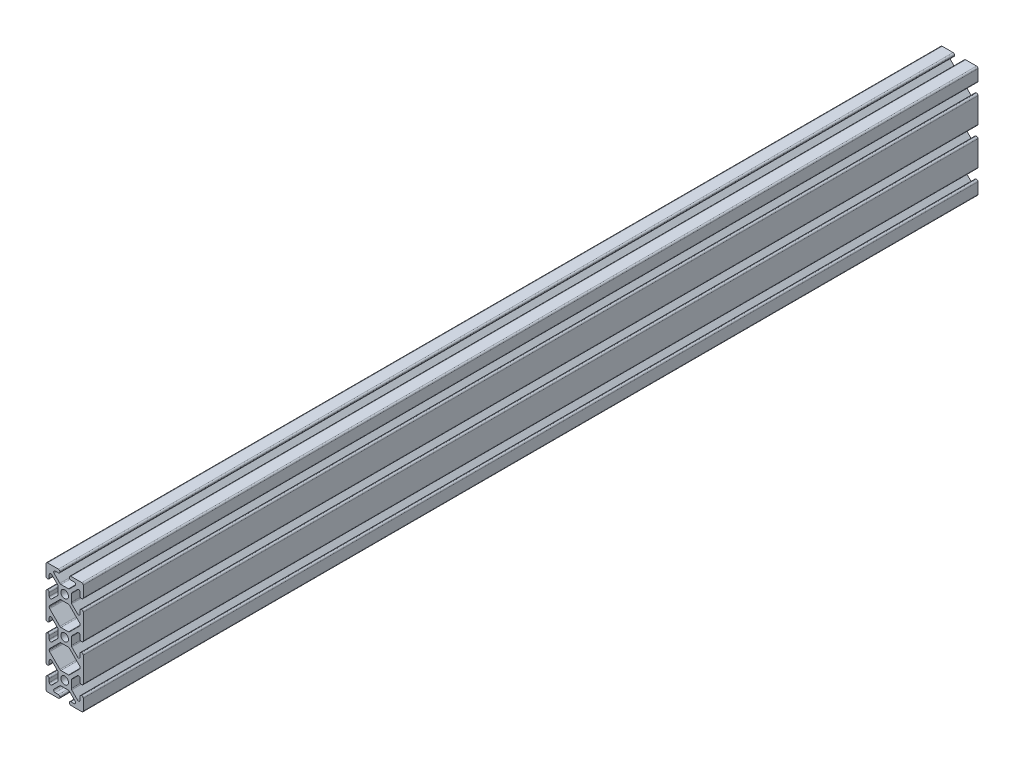
SolidWorks part; units mm, degrees
ref_plane "Front Plane" through (0, 0, 0) normal (0, 0, 1) x (1, 0, 0)
ref_plane "Top Plane" through (0, 0, 0) normal (0, 1, 0) x (1, 0, 0)
ref_plane "Right Plane" through (0, 0, 0) normal (1, 0, 0) x (0, 0, -1)
sketch "Sketch1" plane through (0, 0, 0) normal (0, 0, 1) x (1, 0, 0)
  line L0 (-12.7, 38.1) -> (-12.7, 12.7) construction
  line L1 (-12.7, -38.1) -> (12.7, -38.1) construction
  line L2 (-12.7, 12.7) -> (-12.7, -12.7) construction
  line L3 (-12.7, 38.1) -> (12.7, 38.1) construction
  line L4 (-12.7, -12.7) -> (-12.7, -38.1) construction
  line L5 (-12.7, -38.1) -> (12.7, 38.1) construction
  line L6 (-12.7, 38.1) -> (12.7, -38.1) construction
  line L7 (12.7, 38.1) -> (12.7, 12.7) construction
  line L8 (12.7, 12.7) -> (12.7, -12.7) construction
  line L9 (12.7, -12.7) -> (12.7, -38.1) construction
  line L10 (-12.7, 12.7) -> (12.7, 12.7) construction
  line L11 (-12.7, -12.7) -> (12.7, -12.7) construction
  line L12 (12.7, -12.7) -> (-12.7, -38.1) construction
  line L13 (12.7, -38.1) -> (-12.7, -12.7) construction
  line L14 (0, 38.1) -> (0, -38.1) construction
  line L15 (12.7, 12.7) -> (-12.7, 38.1) construction
  line L16 (12.7, 38.1) -> (-12.7, 12.7) construction
  line L17 (-12.7, 37.084) -> (-12.7, 29.6672)
  line L18 (-11.684, 28.6512) -> (-11.5062, 28.6512)
  line L19 (-10.4902, 29.6672) -> (-10.4902, 31.8748)
  line L20 (-8.7558, 32.5932) -> (-4.8188, 28.6562)
  line L21 (-4.5212, 27.9378) -> (-4.5212, 22.8622)
  line L22 (-4.8188, 22.1438) -> (-8.7558, 18.2068)
  line L23 (-10.4902, 18.9252) -> (-10.4902, 21.1328)
  line L24 (-11.5062, 22.1488) -> (-11.684, 22.1488)
  line L25 (-12.7, 21.1328) -> (-12.7, 4.2672)
  line L26 (-12.7, 0) -> (12.7, 0) construction
  line L27 (-12.7, -25.4) -> (12.7, -25.4) construction
  line L28 (-12.7, 25.4) -> (12.7, 25.4) construction
  line L29 (4.2672, 38.1) -> (11.684, 38.1)
  line L30 (3.2512, 36.9062) -> (3.2512, 37.084)
  line L31 (6.4748, 35.8902) -> (4.2672, 35.8902)
  line L32 (3.2562, 30.2188) -> (7.1932, 34.1558)
  line L33 (-2.5378, 29.9212) -> (2.5378, 29.9212)
  line L34 (-7.1932, 34.1558) -> (-3.2562, 30.2188)
  line L35 (-4.2672, 35.8902) -> (-6.4748, 35.8902)
  line L36 (-3.2512, 37.084) -> (-3.2512, 36.9062)
  line L37 (-11.684, 38.1) -> (-4.2672, 38.1)
  line L38 (4.5212, 2.5378) -> (4.5212, -2.5378)
  line L39 (11.5062, 22.1488) -> (11.684, 22.1488)
  line L40 (10.4902, 18.9252) -> (10.4902, 21.1328)
  line L41 (4.8188, 22.1438) -> (8.7558, 18.2068)
  line L42 (4.5212, 27.9378) -> (4.5212, 22.8622)
  line L43 (8.7558, 32.5932) -> (4.8188, 28.6562)
  line L44 (10.4902, 29.6672) -> (10.4902, 31.8748)
  line L45 (11.684, 28.6512) -> (11.5062, 28.6512)
  line L46 (12.7, 37.084) -> (12.7, 29.6672)
  line L47 (-10.4902, 12.4736) -> (-10.4902, 12.9264)
  line L48 (-10.1926, 13.6448) -> (-3.2562, 20.5812)
  line L49 (-2.5378, 20.8788) -> (2.5378, 20.8788)
  line L50 (10.4902, 12.4736) -> (10.4902, 12.9264)
  line L51 (10.1926, 13.6448) -> (3.2562, 20.5812)
  line L52 (10.1926, 11.7552) -> (3.2562, 4.8188)
  line L53 (-2.5378, 4.5212) -> (2.5378, 4.5212)
  line L54 (-10.1926, 11.7552) -> (-3.2562, 4.8188)
  line L55 (-2.5378, -4.5212) -> (2.5378, -4.5212)
  line L56 (-10.1926, -11.7552) -> (-3.2562, -4.8188)
  line L57 (10.1926, -11.7552) -> (3.2562, -4.8188)
  line L58 (10.4902, -12.4736) -> (10.4902, -12.9264)
  line L59 (10.1926, -13.6448) -> (3.2562, -20.5812)
  line L60 (-2.5378, -20.8788) -> (2.5378, -20.8788)
  line L61 (-10.1926, -13.6448) -> (-3.2562, -20.5812)
  line L62 (-10.4902, -12.4736) -> (-10.4902, -12.9264)
  line L63 (4.8188, -3.2562) -> (8.7558, -7.1932)
  line L64 (11.5062, -22.1488) -> (11.684, -22.1488)
  line L65 (10.4902, -18.9252) -> (10.4902, -21.1328)
  line L66 (4.8188, -22.1438) -> (8.7558, -18.2068)
  line L67 (4.5212, -27.9378) -> (4.5212, -22.8622)
  line L68 (8.7558, -32.5932) -> (4.8188, -28.6562)
  line L69 (10.4902, -29.6672) -> (10.4902, -31.8748)
  line L70 (11.684, -28.6512) -> (11.5062, -28.6512)
  line L71 (12.7, -37.084) -> (12.7, -29.6672)
  line L72 (3.2512, -36.9062) -> (3.2512, -37.084)
  line L73 (6.4748, -35.8902) -> (4.2672, -35.8902)
  line L74 (3.2562, -30.2188) -> (7.1932, -34.1558)
  line L75 (-2.5378, -29.9212) -> (2.5378, -29.9212)
  line L76 (-7.1932, -34.1558) -> (-3.2562, -30.2188)
  line L77 (-4.2672, -35.8902) -> (-6.4748, -35.8902)
  line L78 (-3.2512, -37.084) -> (-3.2512, -36.9062)
  line L79 (-11.684, -38.1) -> (-4.2672, -38.1)
  line L80 (4.2672, -38.1) -> (11.684, -38.1)
  line L81 (4.8188, 3.2562) -> (8.7558, 7.1932)
  line L82 (-11.5062, -22.1488) -> (-11.684, -22.1488)
  line L83 (-10.4902, -18.9252) -> (-10.4902, -21.1328)
  line L84 (-4.8188, -22.1438) -> (-8.7558, -18.2068)
  line L85 (-4.5212, -27.9378) -> (-4.5212, -22.8622)
  line L86 (-8.7558, -32.5932) -> (-4.8188, -28.6562)
  line L87 (-10.4902, -29.6672) -> (-10.4902, -31.8748)
  line L88 (-11.684, -28.6512) -> (-11.5062, -28.6512)
  line L89 (-12.7, -37.084) -> (-12.7, -29.6672)
  line L90 (-4.8188, 3.2562) -> (-8.7558, 7.1932)
  line L91 (-10.4902, 6.4748) -> (-10.4902, 4.2672)
  line L92 (-11.5062, 3.2512) -> (-11.684, 3.2512)
  line L93 (-4.5212, 2.5378) -> (-4.5212, -2.5378)
  line L94 (-12.7, -21.1328) -> (-12.7, -4.2672)
  line L95 (-4.8188, -3.2562) -> (-8.7558, -7.1932)
  line L96 (-10.4902, -6.4748) -> (-10.4902, -4.2672)
  line L97 (-11.5062, -3.2512) -> (-11.684, -3.2512)
  line L98 (10.4902, -6.4748) -> (10.4902, -4.2672)
  line L99 (10.4902, 6.4748) -> (10.4902, 4.2672)
  line L100 (11.5062, 3.2512) -> (11.684, 3.2512)
  line L101 (11.5062, -3.2512) -> (11.684, -3.2512)
  line L102 (12.7, -21.1328) -> (12.7, -4.2672)
  line L103 (12.7, 21.1328) -> (12.7, 4.2672)
  circle A0 centre (0, 25.4) radius 2.6035
  circle A1 centre (0, 0) radius 2.6035
  circle A2 centre (0, -25.4) radius 2.6035
  arc A3 (-12.7, 21.1328) -> (-11.684, 22.1488) centre (-11.684, 21.1328) cw
  arc A4 (-11.5062, 22.1488) -> (-10.4902, 21.1328) centre (-11.5062, 21.1328) cw
  arc A5 (-10.4902, 18.9252) -> (-8.7558, 18.2068) centre (-9.4742, 18.9252) ccw
  arc A6 (-4.8188, 22.1438) -> (-4.5212, 22.8622) centre (-5.5372, 22.8622) ccw
  arc A7 (-4.5212, 27.9378) -> (-4.8188, 28.6562) centre (-5.5372, 27.9378) ccw
  arc A8 (-8.7558, 32.5932) -> (-10.4902, 31.8748) centre (-9.4742, 31.8748) ccw
  arc A9 (-10.4902, 29.6672) -> (-11.5062, 28.6512) centre (-11.5062, 29.6672) cw
  arc A10 (-11.684, 28.6512) -> (-12.7, 29.6672) centre (-11.684, 29.6672) cw
  arc A11 (4.2672, 38.1) -> (3.2512, 37.084) centre (4.2672, 37.084) ccw
  arc A12 (3.2512, 36.9062) -> (4.2672, 35.8902) centre (4.2672, 36.9062) ccw
  arc A13 (6.4748, 35.8902) -> (7.1932, 34.1558) centre (6.4748, 34.8742) cw
  arc A14 (3.2562, 30.2188) -> (2.5378, 29.9212) centre (2.5378, 30.9372) cw
  arc A15 (-2.5378, 29.9212) -> (-3.2562, 30.2188) centre (-2.5378, 30.9372) cw
  arc A16 (-7.1932, 34.1558) -> (-6.4748, 35.8902) centre (-6.4748, 34.8742) cw
  arc A17 (-4.2672, 35.8902) -> (-3.2512, 36.9062) centre (-4.2672, 36.9062) ccw
  arc A18 (-3.2512, 37.084) -> (-4.2672, 38.1) centre (-4.2672, 37.084) ccw
  arc A19 (12.7, 21.1328) -> (11.684, 22.1488) centre (11.684, 21.1328) ccw
  arc A20 (11.5062, 22.1488) -> (10.4902, 21.1328) centre (11.5062, 21.1328) ccw
  arc A21 (10.4902, 18.9252) -> (8.7558, 18.2068) centre (9.4742, 18.9252) cw
  arc A22 (4.8188, 22.1438) -> (4.5212, 22.8622) centre (5.5372, 22.8622) cw
  arc A23 (4.5212, 27.9378) -> (4.8188, 28.6562) centre (5.5372, 27.9378) cw
  arc A24 (8.7558, 32.5932) -> (10.4902, 31.8748) centre (9.4742, 31.8748) cw
  arc A25 (10.4902, 29.6672) -> (11.5062, 28.6512) centre (11.5062, 29.6672) ccw
  arc A26 (11.684, 28.6512) -> (12.7, 29.6672) centre (11.684, 29.6672) ccw
  arc A27 (12.7, 37.084) -> (11.684, 38.1) centre (11.684, 37.084) ccw
  arc A28 (-11.684, 38.1) -> (-12.7, 37.084) centre (-11.684, 37.084) ccw
  arc A29 (-10.1926, 13.6448) -> (-10.4902, 12.9264) centre (-9.4742, 12.9264) ccw
  arc A30 (-2.5378, 20.8788) -> (-3.2562, 20.5812) centre (-2.5378, 19.8628) ccw
  arc A31 (10.1926, 13.6448) -> (10.4902, 12.9264) centre (9.4742, 12.9264) cw
  arc A32 (2.5378, 20.8788) -> (3.2562, 20.5812) centre (2.5378, 19.8628) cw
  arc A33 (10.1926, 11.7552) -> (10.4902, 12.4736) centre (9.4742, 12.4736) ccw
  arc A34 (2.5378, 4.5212) -> (3.2562, 4.8188) centre (2.5378, 5.5372) ccw
  arc A35 (-2.5378, 4.5212) -> (-3.2562, 4.8188) centre (-2.5378, 5.5372) cw
  arc A36 (-10.1926, 11.7552) -> (-10.4902, 12.4736) centre (-9.4742, 12.4736) cw
  arc A37 (2.5378, -4.5212) -> (3.2562, -4.8188) centre (2.5378, -5.5372) cw
  arc A38 (-2.5378, -4.5212) -> (-3.2562, -4.8188) centre (-2.5378, -5.5372) ccw
  arc A39 (10.1926, -11.7552) -> (10.4902, -12.4736) centre (9.4742, -12.4736) cw
  arc A40 (10.1926, -13.6448) -> (10.4902, -12.9264) centre (9.4742, -12.9264) ccw
  arc A41 (2.5378, -20.8788) -> (3.2562, -20.5812) centre (2.5378, -19.8628) ccw
  arc A42 (-2.5378, -20.8788) -> (-3.2562, -20.5812) centre (-2.5378, -19.8628) cw
  arc A43 (-10.1926, -13.6448) -> (-10.4902, -12.9264) centre (-9.4742, -12.9264) cw
  arc A44 (-10.1926, -11.7552) -> (-10.4902, -12.4736) centre (-9.4742, -12.4736) ccw
  arc A45 (12.7, -21.1328) -> (11.684, -22.1488) centre (11.684, -21.1328) cw
  arc A46 (11.5062, -22.1488) -> (10.4902, -21.1328) centre (11.5062, -21.1328) cw
  arc A47 (10.4902, -18.9252) -> (8.7558, -18.2068) centre (9.4742, -18.9252) ccw
  arc A48 (4.8188, -22.1438) -> (4.5212, -22.8622) centre (5.5372, -22.8622) ccw
  arc A49 (4.5212, -27.9378) -> (4.8188, -28.6562) centre (5.5372, -27.9378) ccw
  arc A50 (8.7558, -32.5932) -> (10.4902, -31.8748) centre (9.4742, -31.8748) ccw
  arc A51 (10.4902, -29.6672) -> (11.5062, -28.6512) centre (11.5062, -29.6672) cw
  arc A52 (11.684, -28.6512) -> (12.7, -29.6672) centre (11.684, -29.6672) cw
  arc A53 (4.2672, -38.1) -> (3.2512, -37.084) centre (4.2672, -37.084) cw
  arc A54 (3.2512, -36.9062) -> (4.2672, -35.8902) centre (4.2672, -36.9062) cw
  arc A55 (6.4748, -35.8902) -> (7.1932, -34.1558) centre (6.4748, -34.8742) ccw
  arc A56 (3.2562, -30.2188) -> (2.5378, -29.9212) centre (2.5378, -30.9372) ccw
  arc A57 (-2.5378, -29.9212) -> (-3.2562, -30.2188) centre (-2.5378, -30.9372) ccw
  arc A58 (-7.1932, -34.1558) -> (-6.4748, -35.8902) centre (-6.4748, -34.8742) ccw
  arc A59 (-4.2672, -35.8902) -> (-3.2512, -36.9062) centre (-4.2672, -36.9062) cw
  arc A60 (-3.2512, -37.084) -> (-4.2672, -38.1) centre (-4.2672, -37.084) cw
  arc A61 (12.7, -37.084) -> (11.684, -38.1) centre (11.684, -37.084) cw
  arc A62 (-12.7, -21.1328) -> (-11.684, -22.1488) centre (-11.684, -21.1328) ccw
  arc A63 (-11.5062, -22.1488) -> (-10.4902, -21.1328) centre (-11.5062, -21.1328) ccw
  arc A64 (-10.4902, -18.9252) -> (-8.7558, -18.2068) centre (-9.4742, -18.9252) cw
  arc A65 (-4.8188, -22.1438) -> (-4.5212, -22.8622) centre (-5.5372, -22.8622) cw
  arc A66 (-4.5212, -27.9378) -> (-4.8188, -28.6562) centre (-5.5372, -27.9378) cw
  arc A67 (-8.7558, -32.5932) -> (-10.4902, -31.8748) centre (-9.4742, -31.8748) cw
  arc A68 (-10.4902, -29.6672) -> (-11.5062, -28.6512) centre (-11.5062, -29.6672) ccw
  arc A69 (-11.684, -28.6512) -> (-12.7, -29.6672) centre (-11.684, -29.6672) ccw
  arc A70 (-11.684, -38.1) -> (-12.7, -37.084) centre (-11.684, -37.084) cw
  arc A71 (-4.8188, 3.2562) -> (-4.5212, 2.5378) centre (-5.5372, 2.5378) cw
  arc A72 (-10.4902, 6.4748) -> (-8.7558, 7.1932) centre (-9.4742, 6.4748) cw
  arc A73 (-11.5062, 3.2512) -> (-10.4902, 4.2672) centre (-11.5062, 4.2672) ccw
  arc A74 (-12.7, 4.2672) -> (-11.684, 3.2512) centre (-11.684, 4.2672) ccw
  arc A75 (-4.8188, -3.2562) -> (-4.5212, -2.5378) centre (-5.5372, -2.5378) ccw
  arc A76 (-10.4902, -6.4748) -> (-8.7558, -7.1932) centre (-9.4742, -6.4748) ccw
  arc A77 (-11.5062, -3.2512) -> (-10.4902, -4.2672) centre (-11.5062, -4.2672) cw
  arc A78 (-12.7, -4.2672) -> (-11.684, -3.2512) centre (-11.684, -4.2672) cw
  arc A79 (4.8188, 3.2562) -> (4.5212, 2.5378) centre (5.5372, 2.5378) ccw
  arc A80 (4.8188, -3.2562) -> (4.5212, -2.5378) centre (5.5372, -2.5378) cw
  arc A81 (10.4902, 6.4748) -> (8.7558, 7.1932) centre (9.4742, 6.4748) ccw
  arc A82 (10.4902, -6.4748) -> (8.7558, -7.1932) centre (9.4742, -6.4748) cw
  arc A83 (11.5062, -3.2512) -> (10.4902, -4.2672) centre (11.5062, -4.2672) ccw
  arc A84 (11.5062, 3.2512) -> (10.4902, 4.2672) centre (11.5062, 4.2672) cw
  arc A85 (12.7, -4.2672) -> (11.684, -3.2512) centre (11.684, -4.2672) ccw
  arc A86 (12.7, 4.2672) -> (11.684, 3.2512) centre (11.684, 4.2672) cw
  point P0 (0, 0)
  point P26 (-12.7, 22.1488)
  point P41 (-12.7, 28.6512)
  point P107 (-6.7244, 17.113)
  point P120 (0, 20.8788)
  point P121 (10.4902, 12.7)
  point P132 (-10.4902, 12.7)
  point P249 (-4.5212, 0)
  dimension "D2" = 5.207
  dimension "D8" = 1.016
  dimension "D9" = 3.2512
  dimension "D10" = 1.1049
  dimension "D1" = 25.4
  dimension "D3" = 2.2098
  dimension "D4" = 6.5024
  dimension "D5" = 4.5212
  dimension "D6" = 1.1049
  dimension "D7" = 1.1049
  dimension "D11" = 4.5212
extrude "Main Extrusion" add sketch "Sketch1" along normal mid plane 609.6
sketch "Sketch2" plane through (0, 0, 304.8) normal (0, 0, 1) x (1, 0, 0)
  line L0 (-4.2672, 38.1) -> (-11.684, 38.1) construction
  line L1 (-12.7, -38.1) -> (12.7, -38.1) construction
  line L2 (-12.7, 38.1) -> (-12.7, 12.7) construction
  line L3 (-12.7, 38.1) -> (12.7, 38.1) construction
  line L4 (-12.7, 21.1328) -> (-12.7, 4.2672) construction
  line L5 (-12.7, -38.1) -> (12.7, 38.1) construction
  line L6 (-12.7, 38.1) -> (12.7, -38.1) construction
  line L7 (-12.7, 12.7) -> (-12.7, -12.7) construction
  line L8 (0, 38.1) -> (0, -38.1) construction
  line L9 (-12.7, -4.2672) -> (-12.7, -21.1328) construction
  line L10 (-12.7, -12.7) -> (-12.7, -38.1) construction
  line L11 (12.7, 38.1) -> (12.7, 12.7) construction
  line L12 (12.7, 4.2672) -> (12.7, 21.1328) construction
  line L13 (12.7, 12.7) -> (12.7, -12.7) construction
  line L14 (12.7, -21.1328) -> (12.7, -4.2672) construction
  line L15 (12.7, -12.7) -> (12.7, -38.1) construction
  line L16 (-12.7, 25.4) -> (12.7, 25.4) construction
  line L17 (-12.7, 0) -> (12.7, 0) construction
  line L18 (-12.7, -25.4) -> (12.7, -25.4) construction
  line L19 (-12.7, 12.7) -> (12.7, 12.7) construction
  line L20 (-12.7, -12.7) -> (12.7, -12.7) construction
  line L21 (-3.2512, 36.9062) -> (-3.2512, 37.084) construction
  line L22 (-10.4902, 38.1) -> (-9.4742, 38.1)
  line L23 (-6.477, 38.1) -> (-5.461, 38.1)
  line L24 (-12.7, 38.1) -> (12.7, 12.7) construction
  line L25 (12.7, 12.7) -> (-12.7, -12.7) construction
  line L26 (-12.7, -12.7) -> (12.7, -38.1) construction
  line L27 (-12.7, -38.1) -> (12.7, -12.7) construction
  line L28 (12.7, -12.7) -> (-12.7, 12.7) construction
  line L29 (-12.7, 12.7) -> (12.7, 38.1) construction
  line L30 (6.477, 38.1) -> (5.461, 38.1)
  line L31 (10.4902, 38.1) -> (9.4742, 38.1)
  line L32 (-12.7, 14.9098) -> (-12.7, 15.9258)
  line L33 (-12.7, 18.923) -> (-12.7, 19.939)
  line L34 (-12.7, 31.877) -> (-12.7, 30.861)
  line L35 (-12.7, 35.8902) -> (-12.7, 34.8742)
  line L36 (12.7, 35.8902) -> (12.7, 34.8742)
  line L37 (12.7, 31.877) -> (12.7, 30.861)
  line L38 (12.7, 18.923) -> (12.7, 19.939)
  line L39 (12.7, 14.9098) -> (12.7, 15.9258)
  line L40 (12.7, 10.4902) -> (12.7, 9.4742)
  line L41 (12.7, 6.477) -> (12.7, 5.461)
  line L42 (-12.7, 10.4902) -> (-12.7, 9.4742)
  line L43 (-12.7, 6.477) -> (-12.7, 5.461)
  line L44 (12.7, -6.477) -> (12.7, -5.461)
  line L45 (12.7, -10.4902) -> (12.7, -9.4742)
  line L46 (12.7, -14.9098) -> (12.7, -15.9258)
  line L47 (12.7, -18.923) -> (12.7, -19.939)
  line L48 (12.7, -31.877) -> (12.7, -30.861)
  line L49 (12.7, -35.8902) -> (12.7, -34.8742)
  line L50 (10.4902, -38.1) -> (9.4742, -38.1)
  line L51 (6.477, -38.1) -> (5.461, -38.1)
  line L52 (-6.477, -38.1) -> (-5.461, -38.1)
  line L53 (-10.4902, -38.1) -> (-9.4742, -38.1)
  line L54 (-12.7, -35.8902) -> (-12.7, -34.8742)
  line L55 (-12.7, -31.877) -> (-12.7, -30.861)
  line L56 (-12.7, -18.923) -> (-12.7, -19.939)
  line L57 (-12.7, -14.9098) -> (-12.7, -15.9258)
  line L58 (-12.7, -10.4902) -> (-12.7, -9.4742)
  line L59 (-12.7, -6.477) -> (-12.7, -5.461)
  arc A0 (-10.4902, 38.1) -> (-9.4742, 38.1) centre (-9.9822, 38.1) ccw
  arc A1 (-6.477, 38.1) -> (-5.461, 38.1) centre (-5.969, 38.1) ccw
  arc A2 (6.477, 38.1) -> (5.461, 38.1) centre (5.969, 38.1) cw
  arc A3 (10.4902, 38.1) -> (9.4742, 38.1) centre (9.9822, 38.1) cw
  arc A4 (-12.7, 14.9098) -> (-12.7, 15.9258) centre (-12.7, 15.4178) ccw
  arc A5 (-12.7, 18.923) -> (-12.7, 19.939) centre (-12.7, 19.431) ccw
  arc A6 (-12.7, 31.877) -> (-12.7, 30.861) centre (-12.7, 31.369) cw
  arc A7 (-12.7, 35.8902) -> (-12.7, 34.8742) centre (-12.7, 35.3822) cw
  arc A8 (12.7, 35.8902) -> (12.7, 34.8742) centre (12.7, 35.3822) ccw
  arc A9 (12.7, 31.877) -> (12.7, 30.861) centre (12.7, 31.369) ccw
  arc A10 (12.7, 18.923) -> (12.7, 19.939) centre (12.7, 19.431) cw
  arc A11 (12.7, 14.9098) -> (12.7, 15.9258) centre (12.7, 15.4178) cw
  arc A12 (12.7, 10.4902) -> (12.7, 9.4742) centre (12.7, 9.9822) ccw
  arc A13 (12.7, 6.477) -> (12.7, 5.461) centre (12.7, 5.969) ccw
  arc A14 (-12.7, 10.4902) -> (-12.7, 9.4742) centre (-12.7, 9.9822) cw
  arc A15 (-12.7, 6.477) -> (-12.7, 5.461) centre (-12.7, 5.969) cw
  arc A16 (12.7, -6.477) -> (12.7, -5.461) centre (12.7, -5.969) cw
  arc A17 (12.7, -10.4902) -> (12.7, -9.4742) centre (12.7, -9.9822) cw
  arc A18 (12.7, -14.9098) -> (12.7, -15.9258) centre (12.7, -15.4178) ccw
  arc A19 (12.7, -18.923) -> (12.7, -19.939) centre (12.7, -19.431) ccw
  arc A20 (12.7, -31.877) -> (12.7, -30.861) centre (12.7, -31.369) cw
  arc A21 (12.7, -35.8902) -> (12.7, -34.8742) centre (12.7, -35.3822) cw
  arc A22 (10.4902, -38.1) -> (9.4742, -38.1) centre (9.9822, -38.1) ccw
  arc A23 (6.477, -38.1) -> (5.461, -38.1) centre (5.969, -38.1) ccw
  arc A24 (-6.477, -38.1) -> (-5.461, -38.1) centre (-5.969, -38.1) cw
  arc A25 (-10.4902, -38.1) -> (-9.4742, -38.1) centre (-9.9822, -38.1) cw
  arc A26 (-12.7, -35.8902) -> (-12.7, -34.8742) centre (-12.7, -35.3822) ccw
  arc A27 (-12.7, -31.877) -> (-12.7, -30.861) centre (-12.7, -31.369) ccw
  arc A28 (-12.7, -18.923) -> (-12.7, -19.939) centre (-12.7, -19.431) cw
  arc A29 (-12.7, -14.9098) -> (-12.7, -15.9258) centre (-12.7, -15.4178) cw
  arc A30 (-12.7, -10.4902) -> (-12.7, -9.4742) centre (-12.7, -9.9822) ccw
  arc A31 (-12.7, -6.477) -> (-12.7, -5.461) centre (-12.7, -5.969) ccw
  point P0 (0, 0)
  dimension "D1" = 0.508
  dimension "D2" = 2.2098
  dimension "D3" = 2.2098
